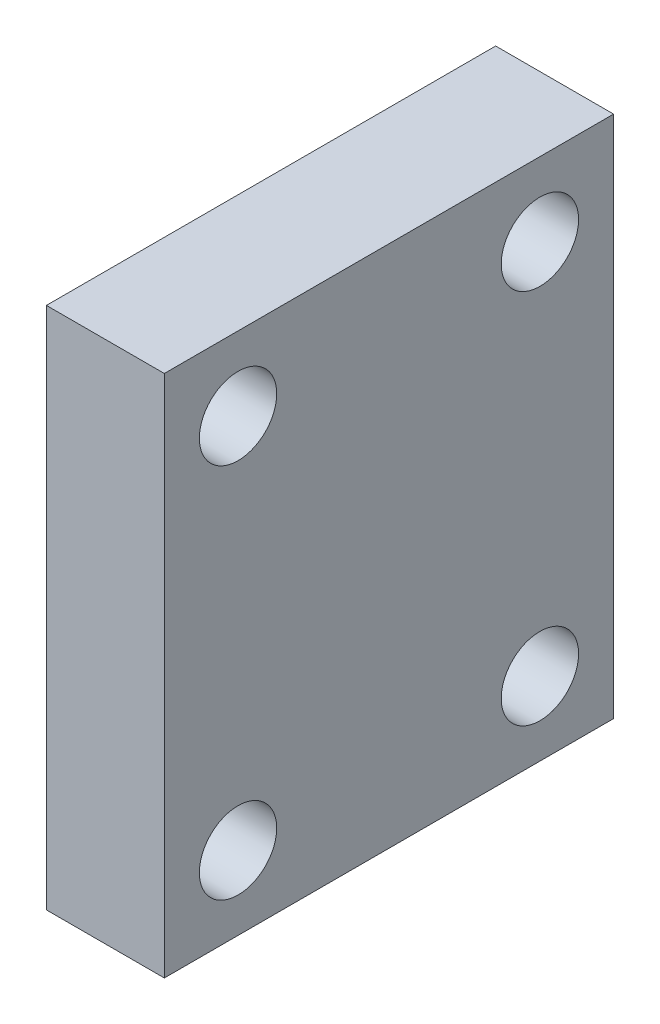
SolidWorks part; units mm, degrees
ref_plane "Front Plane" through (0, 0, 0) normal (1, 0, 0) x (0, 1, 0)
ref_plane "Top Plane" through (0, 0, 0) normal (0, 0, 1) x (0, 1, 0)
ref_plane "Right Plane" through (0, 0, 0) normal (0, 1, 0) x (-1, 0, 0)
sketch "Sketch1" plane through (0, 0, 0) normal (1, 0, 0) x (0, 1, 0)
  line L1 (0, 0) -> (112.776, 0)
  line L2 (0, 0) -> (0, 96.774)
  line L3 (0, 96.774) -> (112.776, 96.774)
  line L4 (112.776, 0) -> (112.776, 96.774)
extrude "Boss-Extrude1" add sketch "Sketch1" along normal blind 25.4
sketch "Sketch2" plane through (0, 0, 0) normal (1, 0, 0) x (0, 1, 0)
  circle A0 centre (15.875, 15.875) radius 8.3344
  circle A1 centre (96.901, 15.875) radius 8.3344
  circle A2 centre (15.875, 80.899) radius 8.3344
  circle A3 centre (96.901, 80.899) radius 8.3344
extrude "Cut-Extrude2" cut sketch "Sketch2" along normal through all
sketch "Sketch3" plane through (0, 0, 0) normal (1, 0, 0) x (0, 1, 0)
  circle A0 centre (28.575, 48.387) radius 11.5094
  circle A1 centre (74.549, 48.387) radius 11.5094
extrude "Cut-Extrude3" cut sketch "Sketch3" along normal blind 12.7
sketch "Sketch4" plane through (0, 0, 0) normal (1, 0, 0) x (0, 1, 0)
  circle A0 centre (38.227, 48.387) radius 11.5094
  circle A1 centre (84.201, 48.387) radius 11.5094
extrude "Cut-Extrude4" cut sketch "Sketch4" along normal blind 12.7
sketch "Sketch5" plane through (0, 0, 0) normal (1, 0, 0) x (0, 1, 0)
  circle A0 centre (38.227, 48.387) radius 16.6497
  circle A1 centre (84.201, 48.387) radius 16.6497
extrude "Cut-Extrude5" cut sketch "Sketch5" along normal blind 2.8194
sketch "Sketch6" plane through (0, 0, 0) normal (1, 0, 0) x (0, 1, 0)
  circle A0 centre (105.537, 48.387) radius 3.5719
  circle A1 centre (56.515, 15.875) radius 3.5719
extrude "Cut-Extrude6" cut sketch "Sketch6" along normal blind 7.874
sketch "Sketch7" plane through (0, 0, 0) normal (1, 0, 0) x (0, 1, 0)
  circle A0 centre (38.227, 48.387) radius 16.6497
sketch "Sketch8" plane through (0, 0, 0) normal (1, 0, 0) x (0, 1, 0)
  circle A0 centre (7.239, 48.387) radius 3.175
  circle A1 centre (56.261, 80.899) radius 3.175
extrude "Cut-Extrude9" cut sketch "Sketch8" along normal blind 7.874
